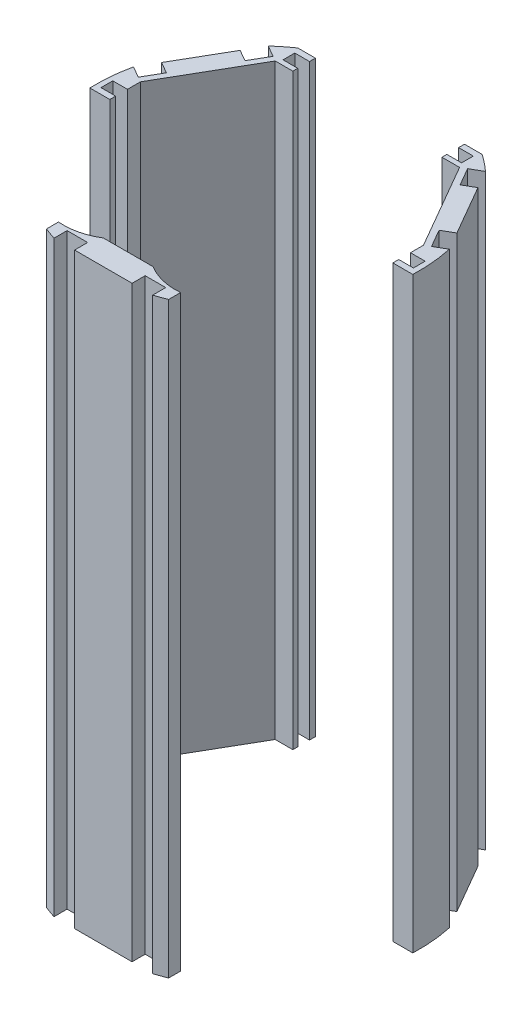
SolidWorks part; units mm, degrees
ref_plane "Front Plane" through (0, 0, 0) normal (0, 0, 1) x (1, 0, 0)
ref_plane "Top Plane" through (0, 0, 0) normal (0, 1, 0) x (1, 0, 0)
ref_plane "Right Plane" through (0, 0, 0) normal (1, 0, 0) x (0, 0, -1)
sketch "Sketch1" plane through (0, 0, 0) normal (0, 1, 0) x (1, 0, 0)
  line L0 (0, 0) -> (0, -30.5) construction
  line L1 (-7.894, -24.4607) -> (-5.394, -24.4607)
  line L2 (0, 0) -> (-7.894, -29.4607) construction
  line L3 (-7.894, -29.4607) -> (7.894, -29.4607) construction
  line L4 (7.894, -29.4607) -> (7.894, -24.4607)
  line L5 (-7.894, -29.4607) -> (-7.894, -24.4607)
  line L6 (7.894, -24.4607) -> (5.394, -24.4607)
  line L7 (-5.394, -24.4607) -> (-5.394, -27.9849)
  line L8 (-8.394, -26.1876) -> (8.394, -26.1876) construction
  line L9 (5.394, -27.9849) -> (5.394, -24.4607)
  line L10 (5.394, -24.4607) -> (5.5317, -24.5711)
  line L11 (-8.394, -26.1876) -> (-8.394, -23.9607)
  line L12 (-8.394, -23.9607) -> (-4.894, -23.9607)
  line L13 (-4.894, -23.9607) -> (-4.894, -26.1876)
  line L14 (4.894, -26.1876) -> (4.894, -23.9607)
  line L15 (4.894, -23.9607) -> (8.394, -23.9607)
  line L16 (8.394, -23.9607) -> (8.394, -26.1876)
  line L17 (-4.8497, -26.1876) -> (4.9382, -26.1876)
  line L18 (-20.2543, 17.2938) -> (-25.1482, 8.8172)
  line L19 (-18.3036, 16.2187) -> (-20.2321, 17.3321)
  line L20 (-25.1261, 8.8555) -> (-23.1976, 7.7421)
  line L21 (-23.1976, 7.7421) -> (-24.9476, 4.711)
  line L22 (-24.9476, 4.711) -> (-26.8761, 5.8244)
  line L23 (-16.5536, 19.2498) -> (-18.3036, 16.2187)
  line L24 (-18.4821, 20.3632) -> (-16.5536, 19.2498)
  line L25 (25.104, 8.8938) -> (20.21, 17.3704)
  line L26 (23.1976, 7.7421) -> (25.1261, 8.8555)
  line L27 (20.2321, 17.3321) -> (18.3036, 16.2187)
  line L28 (18.3036, 16.2187) -> (16.5536, 19.2498)
  line L29 (16.5536, 19.2498) -> (18.4821, 20.3632)
  line L30 (24.9476, 4.711) -> (23.1976, 7.7421)
  line L31 (24.9476, 4.711) -> (26.8761, 5.8244)
  line L32 (0, 0) -> (-30.5, 0) construction
  line L33 (0, 0) -> (30.5, 0) construction
  line L34 (-24.0816, 4.211) -> (-15.6876, 18.7498)
  line L35 (-24.0816, 4.211) -> (-24.0816, -1)
  line L36 (-24.0816, -1) -> (-27.4818, -1)
  line L37 (15.6876, 18.7498) -> (24.0816, 4.211)
  line L38 (-24.0816, 0) -> (-26.5816, 0)
  line L39 (-24.0816, 0) -> (-24.0816, 2)
  line L40 (-24.0816, 2) -> (-26.5816, 2)
  line L41 (-26.5816, 0) -> (-26.5816, 2)
  line L42 (24.0816, 4.211) -> (24.0816, -1)
  line L43 (24.0816, -1) -> (27.4818, -1)
  line L44 (10.394, -25.4601) -> (10.394, -23.4207)
  line L45 (24.0816, 0) -> (26.5816, 0)
  line L46 (24.0816, 0) -> (24.0816, 2)
  line L47 (24.0816, 2) -> (26.5816, 2)
  line L48 (26.5816, 0) -> (26.5816, 2)
  line L49 (-15.6876, 18.7498) -> (-12.6876, 18.7498)
  line L50 (-15.6876, 18.7498) -> (-15.6876, 22.5865)
  line L51 (-15.6876, 22.5865) -> (-12.6876, 22.5865)
  line L52 (-12.6876, 18.7498) -> (-12.6876, 22.5865)
  line L53 (-12.6876, 19.5865) -> (-15.1876, 19.5865)
  line L54 (-12.6876, 19.5865) -> (-12.6876, 21.5865)
  line L55 (-12.6876, 21.5865) -> (-15.1876, 21.5865)
  line L56 (-15.1876, 19.5865) -> (-15.1876, 21.5865)
  line L57 (15.6876, 18.7498) -> (12.6876, 18.7498)
  line L58 (15.6876, 18.7498) -> (15.6876, 22.5865)
  line L59 (15.6876, 22.5865) -> (12.6876, 22.5865)
  line L60 (12.6876, 18.7498) -> (12.6876, 22.5865)
  line L61 (12.6876, 21.5865) -> (15.1876, 21.5865)
  line L62 (12.6876, 21.5865) -> (12.6876, 19.5865)
  line L63 (12.6876, 19.5865) -> (15.1876, 19.5865)
  line L64 (15.1876, 21.5865) -> (15.1876, 19.5865)
  line L65 (-10.394, -25.4601) -> (-10.394, -23.4207)
  line L66 (-4.2322, -21.9607) -> (4.2322, -21.9607)
  line L67 (26.8761, 5.8244) -> (24.9476, 4.711) [skipped]
  line L68 (25.104, 8.8938) -> (25.1261, 8.8555)
  line L69 (-20.2543, 17.2938) -> (-20.2321, 17.3321)
  line L70 (-4.8497, -26.1876) -> (-4.894, -26.1876)
  circle A0 centre (0, 0) radius 27.5
  circle A1 centre (0, 0) radius 28.5
  circle A2 centre (0, 0) radius 30.5
  circle A3 centre (9.5, -13.4607) radius 10
  circle A4 centre (-9.5, -13.4607) radius 10
  point P25 (-24.0816, 4.211)
  point P48 (0, 0)
  point P49 (-15.6876, 18.7498)
  point P52 (-24.0816, 0)
  point P59 (24.0816, 4.211)
  point P60 (15.6876, 18.7498)
  point P63 (24.0816, 0)
  point P70 (25.3316, 2)
  dimension "D1" = 55
  dimension "D2" = 57
  dimension "D3" = 61
  dimension "D36" = 9.5
  dimension "D37" = 9.5
  dimension "D38" = 0
  dimension "D41" = 20
  dimension "D42" = 20
  dimension "D4" = 2.5
  dimension "D5" = 15
  dimension "D6" = 5
  dimension "D7" = 5
  dimension "D8" = 2.5
  dimension "D9" = 0.5
  dimension "D10" = 0.5
  dimension "D11" = 0.5
  dimension "D12" = 0.5
  dimension "D13" = 0.5
  dimension "D15" = 1
  dimension "D16" = 0
  dimension "D17" = 0
  dimension "D18" = 1
  dimension "D19" = 1
  dimension "D20" = 2.5
  dimension "D21" = 2
  dimension "D23" = 1
  dimension "D24" = 0
  dimension "D25" = 1
  dimension "D26" = 1
  dimension "D27" = 2.5
  dimension "D28" = 2
  dimension "D29" = 27.5
  dimension "D30" = 3
  dimension "D31" = 2
  dimension "D32" = 2.5
  dimension "D33" = 1
  dimension "D34" = 3
  dimension "D35" = 2.5
  dimension "D39" = 10.5
  dimension "D40" = 2
  dimension "D43" = 2
  dimension "D44" = 2
  dimension "D14" = 3
extrude "Boss-Extrude1" add sketch "Sketch1" along normal blind 100 contours A4 L65 A0 L11 L12 L13 L70 L17 L14 L15 L16 L44 A3 L66 | L43 A0 L31 L30 L26 L68 L25 L27 L28 L29 L58 L37 L42 L47 L48 L45 | L50 A0 L24 L23 L19 L69 L18 L20 L21 L22 L36 L35 L38 L41 L40 L34 | L53 L56 L55 L52 L51 L50 L49 | L61 L64 L63 L60 L57 L58 L59
